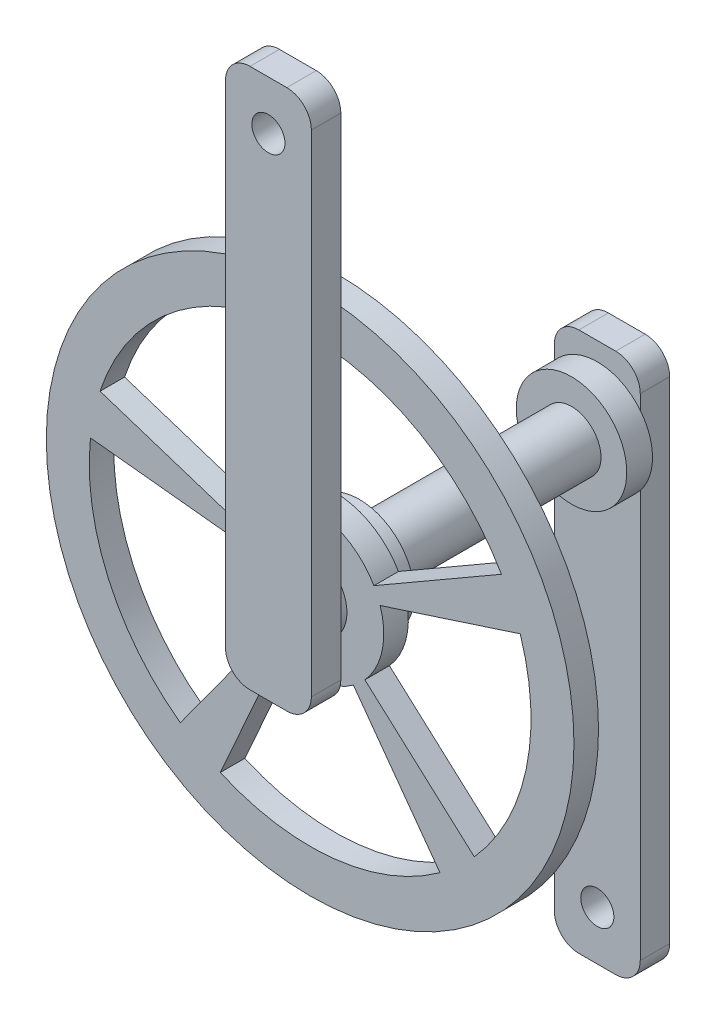
SolidWorks part; units mm, degrees
material "6061 Alloy"
ref_plane "Front Plane" through (0, 0, 0) normal (0, 0, 1) x (1, 0, 0)
ref_plane "Top Plane" through (0, 0, 0) normal (0, 1, 0) x (1, 0, 0)
ref_plane "Right Plane" through (0, 0, 0) normal (1, 0, 0) x (0, 0, -1)
sketch "Sketch1" plane through (0, 0, 0) normal (0, 0, 1) x (1, 0, 0)
  circle A0 centre (0, 0) radius 12
  dimension "D1" = 24
extrude "Boss-Extrude1" add sketch "Sketch1" along normal blind 36 and the other way blind 50.5
sketch "Sketch6" plane through (0, 0, -50.5) normal (0, 0, -1) x (-1, 0, 0)
  circle A0 centre (0, 0) radius 22.5
  dimension "D1" = 45
extrude "Boss-Extrude6" add sketch "Sketch6" along normal blind 10.5
sketch "Sketch7" plane through (0, 0, 36) normal (0, 0, 1) x (1, 0, 0)
  circle A0 centre (0, 0) radius 22.5
  dimension "D1" = 45
extrude "Boss-Extrude7" add sketch "Sketch7" along normal blind 10
sketch "Sketch2" plane through (0, 0, -61) normal (0, 0, -1) x (-1, 0, 0)
  line L1 (-7.5, -190) -> (7.5, -190)
  line L2 (-17.5, -180) -> (-17.5, 20)
  line L3 (-7.5, 30) -> (7.5, 30)
  line L4 (17.5, -180) -> (17.5, 20)
  circle A0 centre (0, -170) radius 6.75
  arc A1 (7.5, -190) -> (17.5, -180) centre (7.5, -180) ccw
  arc A2 (-7.5, -190) -> (-17.5, -180) centre (-7.5, -180) cw
  arc A3 (7.5, 30) -> (17.5, 20) centre (7.5, 20) cw
  arc A4 (-7.5, 30) -> (-17.5, 20) centre (-7.5, 20) ccw
  point P4 (0, 30)
  point P11 (17.5, -190)
  point P16 (17.5, 30)
  point P19 (-17.5, 30)
  point P20 (0, 0)
  dimension "D4" = 13.5
  dimension "D6" = 10
  dimension "D1" = 30
  dimension "D2" = 220
  dimension "D3" = 35
  dimension "D5" = 170
extrude "Boss-Extrude2" add sketch "Sketch2" along normal blind 12
sketch "Sketch3" plane through (0, 0, 46) normal (0, 0, 1) x (1, 0, 0)
  line L2 (0, 30) -> (0, 90)
  line L3 (25.9808, 15) -> (77.9423, 45)
  line L4 (28.5317, 9.2705) -> (85.5951, 27.8115)
  line L5 (22.2943, -20.0739) -> (66.883, -60.2218)
  line L6 (17.6336, -24.2705) -> (52.9007, -72.8115)
  line L7 (-12.2021, -27.4064) -> (-36.6063, -82.2191)
  line L8 (-17.6336, -24.2705) -> (-52.9007, -72.8115)
  line L9 (-29.8357, 3.1359) -> (-89.507, 9.4076)
  line L10 (-28.5317, 9.2705) -> (-85.5951, 27.8115)
  line L11 (-6.2374, 29.3444) -> (-18.7121, 88.0333)
  circle A0 centre (0, 0) radius 107.5
  arc A1 (0, 90) -> (77.9423, 45) centre (0, 0) cw
  arc A2 (0, 30) -> (25.9808, 15) centre (0, 0) cw
  arc A3 (28.5317, 9.2705) -> (22.2943, -20.0739) centre (0, 0) cw
  arc A4 (85.5951, 27.8115) -> (66.883, -60.2218) centre (0, 0) cw
  arc A5 (17.6336, -24.2705) -> (-12.2021, -27.4064) centre (0, 0) cw
  arc A6 (52.9007, -72.8115) -> (-36.6063, -82.2191) centre (0, 0) cw
  arc A7 (-17.6336, -24.2705) -> (-29.8357, 3.1359) centre (0, 0) cw
  arc A8 (-52.9007, -72.8115) -> (-89.507, 9.4076) centre (0, 0) cw
  arc A9 (-28.5317, 9.2705) -> (-6.2374, 29.3444) centre (0, 0) cw
  arc A10 (-85.5951, 27.8115) -> (-18.7121, 88.0333) centre (0, 0) cw
  point P26 (0, 0)
  dimension "D1" = 215
  dimension "D2" = 90
  dimension "D3" = 60
  dimension "D4" = 30
  dimension "D5" = 60
  dimension "D6" = 5
extrude "Boss-Extrude3" add sketch "Sketch3" along normal blind 10
sketch "Sketch5" plane through (0, 0, 56) normal (0, 0, 1) x (1, 0, 0)
  circle A0 centre (0, 0) radius 15
  dimension "D1" = 30
extrude "Boss-Extrude5" add sketch "Sketch5" along normal blind 5
sketch "Sketch4" plane through (0, 0, 61) normal (0, 0, 1) x (1, 0, 0)
  line L1 (-7.5, -30) -> (7.5, -30)
  line L2 (-17.5, -20) -> (-17.5, 180)
  line L3 (-7.5, 190) -> (7.5, 190)
  line L4 (17.5, -20) -> (17.5, 180)
  circle A0 centre (0, 170) radius 6.75
  arc A1 (7.5, 190) -> (17.5, 180) centre (7.5, 180) cw
  arc A2 (-7.5, 190) -> (-17.5, 180) centre (-7.5, 180) ccw
  arc A3 (17.5, -20) -> (7.5, -30) centre (7.5, -20) cw
  arc A4 (-17.5, -20) -> (-7.5, -30) centre (-7.5, -20) ccw
  point P7 (0, -30)
  point P10 (17.5, 190)
  point P13 (-17.5, 190)
  point P16 (17.5, -30)
  dimension "D5" = 10
  dimension "D6" = 13.5
  dimension "D1" = 30
  dimension "D2" = 170
  dimension "D3" = 220
  dimension "D4" = 35
extrude "Boss-Extrude4" add sketch "Sketch4" along normal blind 12
